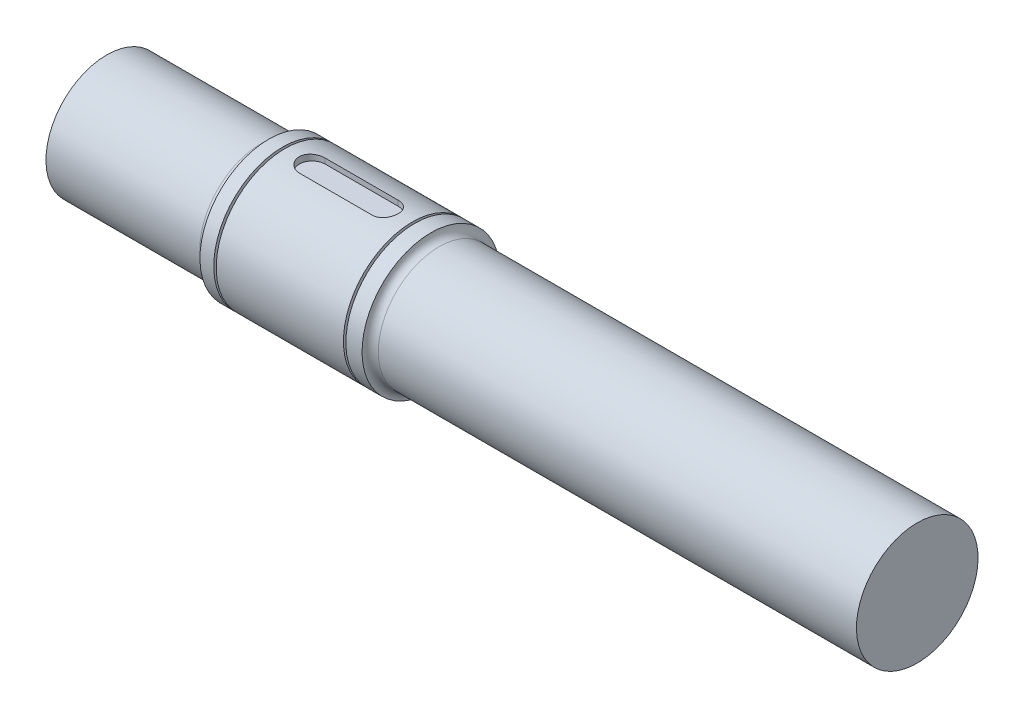
SolidWorks part; units mm, degrees
ref_plane "Front" through (0, 0, 0) normal (0, 0, 1) x (1, 0, 0)
ref_plane "Top" through (0, 0, 0) normal (0, 1, 0) x (1, 0, 0)
ref_plane "Right" through (0, 0, 0) normal (1, 0, 0) x (0, 0, -1)
sketch "Esquisse1" plane through (0, 0, 0) normal (0, 0, 1) x (1, 0, 0)
  line L0 (0, 0) -> (0, 37.5)
  line L1 (0, 37.5) -> (95, 37.5)
  line L3 (100, 42.5) -> (200, 42.5)
  line L5 (205, 37.5) -> (500, 37.5)
  line L6 (500, 37.5) -> (500, 0)
  line L7 (500, 0) -> (0, 0)
  arc A0 (100, 42.5) -> (95, 37.5) centre (95, 42.5) cw
  arc A1 (200, 42.5) -> (205, 37.5) centre (205, 42.5) ccw
  dimension "D4" = 5
  dimension "D6" = 5
  dimension "D1" = 37.5
  dimension "D2" = 100
  dimension "D3" = 500
  dimension "D5" = 42.5
  dimension "D7" = 100
revolve "Révolution1" add sketch "Esquisse1" angle 360 about L7
ref_plane "Plan1" through (110, 0, 0) normal (1, 0, 0) x (0, 0, -1)
ref_plane "Plan2" through (190, 0, 0) normal (1, 0, 0) x (0, 0, -1)
sketch "Esquisse2" plane through (110, 0, 0) normal (1, 0, 0) x (0, 0, -1)
  circle A0 centre (0, 0) radius 42.5 construction
  circle A2 centre (0, 0) radius 42.5
  circle A3 centre (0, 0) radius 39.5
  dimension "D1" = 3
extrude "Enlèv. mat.-Extru.1" cut sketch "Esquisse2" against normal blind 1.5
sketch "Esquisse3" plane through (190, 0, 0) normal (1, 0, 0) x (0, 0, -1)
  circle A0 centre (0, 0) radius 42.5 construction
  circle A1 centre (0, 0) radius 42.5
  circle A2 centre (0, 0) radius 39.5
  dimension "D1" = 3
extrude "Enlèv. mat.-Extru.2" cut sketch "Esquisse3" against normal blind 1.5
ref_plane "Plan3" through (0, 42.5, 0) normal (0, 1, 0) x (1, 0, 0)
sketch "Esquisse4" plane through (0, 42.5, 0) normal (0, 1, 0) x (1, 0, 0)
  line L0 (149.25, 42.5) -> (149.25, 0) construction
  line L1 (188.5, 42.5) -> (110, 42.5) construction
  line L2 (126.75, 0) -> (171.75, 0) construction
  line L3 (126.75, 8) -> (171.75, 8)
  line L4 (126.75, -8) -> (171.75, -8)
  arc A0 (126.75, 8) -> (126.75, -8) centre (126.75, 0) ccw
  arc A1 (171.75, -8) -> (171.75, 8) centre (171.75, 0) ccw
  point P6 (149.25, 0)
  dimension "D2" = 8
  dimension "D1" = 45
extrude "Enlèv. mat.-Extru.3" cut sketch "Esquisse4" against normal blind 4
ref_plane "Plan4" through (0, 42.5, 0) normal (0, 1, 0) x (1, 0, 0)
sketch "Esquisse5" plane through (0, 42.5, 0) normal (0, 1, 0) x (1, 0, 0)
  line L0 (500, 0) -> (435, 0) construction
  line L1 (500, -37.5) -> (500, 37.5) construction
  dimension "D1" = 65
